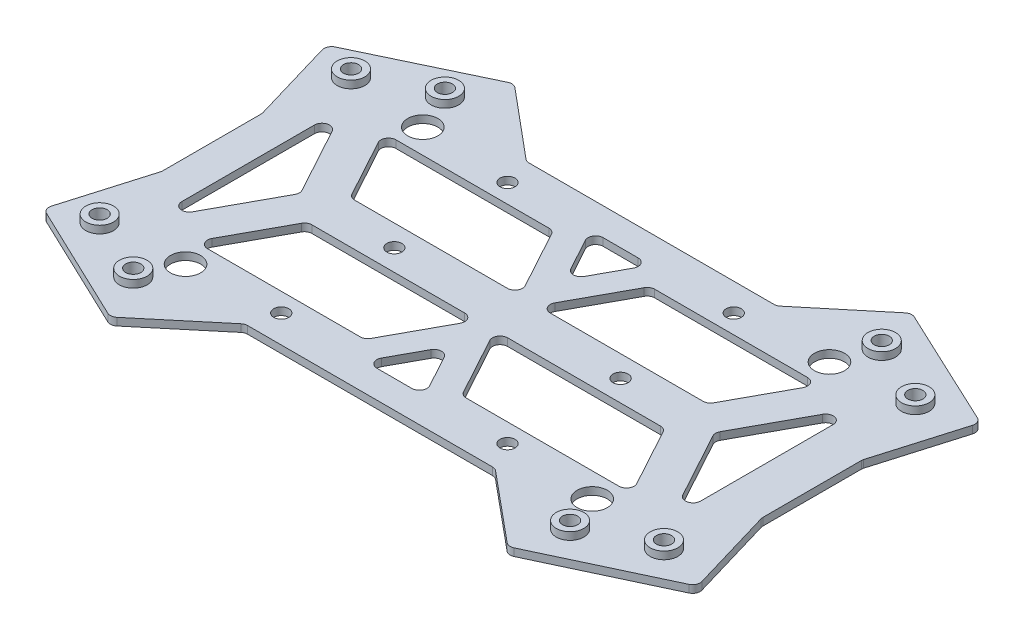
SolidWorks part; units mm, degrees
material "Thornel VCB-20 Carbon Cloth"
ref_plane "Front Plane" through (0, 0, 0) normal (0, 0, 1) x (1, 0, 0)
ref_plane "Top Plane" through (0, 0, 0) normal (0, 1, 0) x (1, 0, 0)
ref_plane "Right Plane" through (0, 0, 0) normal (1, 0, 0) x (0, 0, -1)
sketch "Sketch1" plane through (0, 0, 0) normal (0, 1, 0) x (1, 0, 0)
  line L9 (-39.7187, 39.786) -> (-64.1438, 28.1459) construction
  line L10 (-24.6676, 28.349) -> (-38.1116, 39.583) construction
  line L11 (25.0086, 28) -> (-23.7058, 28) construction
  line L12 (39.5171, 39.5917) -> (25.9666, 28.3457) construction
  line L13 (65.9472, 28.1421) -> (41.1122, 39.7954) construction
  line L14 (-39.7187, 39.786) -> (-64.1438, 28.1459)
  line L22 (-24.6676, 28.349) -> (-38.1116, 39.583)
  line L23 (25.0086, 28) -> (-23.7058, 28)
  line L24 (39.5171, 39.5917) -> (25.9666, 28.3457)
  line L25 (65.9472, 28.1421) -> (41.1122, 39.7954)
  line L26 (-123, 23) -> (-123, -23) construction
  line L27 (100.1, 23) -> (100.1, -23) construction
  line L28 (66.5844, 28) -> (94.45, 28) construction
  line L29 (-64.7892, 28) -> (-118, 28) construction
  line L30 (-123, 23) -> (-123, -23) construction
  line L31 (100.1, 23) -> (100.1, -23) construction
  line L32 (66.5844, 28) -> (94.45, 28) construction
  line L33 (-64.7892, 28) -> (-118, 28) construction
  line L34 (0, 0) -> (0, 28) construction
  line L35 (0, 0) -> (100.1, 0) construction
  line L36 (0, 0) -> (-123, 0) construction
  line L37 (60.6, 0) -> (60.6, 10)
  line L38 (65.9472, 28.1421) -> (60.6, 10)
  line L39 (-58.7938, 0) -> (-58.7938, 10)
  line L40 (-64.1438, 28.1459) -> (-58.7938, 10)
  line L41 (-58.7938, 0) -> (60.6, 0)
  arc A0 (-38.1116, 39.583) -> (-39.7187, 39.786) centre (-39.0734, 38.4319) ccw construction
  arc A1 (-38.1116, 39.583) -> (-39.7187, 39.786) centre (-39.0734, 38.4319) ccw
  circle A14 centre (-43.45, 31) radius 1.5 construction
  circle A15 centre (-56.13, 25) radius 1.5 construction
  arc A16 (-64.7892, 28) -> (-64.1438, 28.1459) centre (-64.7892, 29.5) ccw construction
  arc A29 (-24.6676, 28.349) -> (-23.7058, 28) centre (-23.7058, 29.5) ccw construction
  circle A30 centre (56.13, 25) radius 1.5 construction
  circle A31 centre (43.45, 31) radius 1.5 construction
  arc A32 (25.0086, 28) -> (25.9666, 28.3457) centre (25.0086, 29.5) ccw construction
  arc A33 (41.1122, 39.7954) -> (39.5171, 39.5917) centre (40.475, 38.4375) ccw construction
  arc A34 (65.9472, 28.1421) -> (66.5844, 28) centre (66.5844, 29.5) ccw construction
  circle A35 centre (-43.45, 31) radius 1.5
  circle A36 centre (-56.13, 25) radius 1.5
  arc A37 (-64.7892, 28) -> (-64.1438, 28.1459) centre (-64.7892, 29.5) ccw construction
  arc A39 (-24.6676, 28.349) -> (-23.7058, 28) centre (-23.7058, 29.5) ccw
  circle A40 centre (56.13, 25) radius 1.5
  circle A41 centre (43.45, 31) radius 1.5
  arc A42 (25.0086, 28) -> (25.9666, 28.3457) centre (25.0086, 29.5) ccw
  arc A43 (41.1122, 39.7954) -> (39.5171, 39.5917) centre (40.475, 38.4375) ccw
  arc A44 (65.9472, 28.1421) -> (66.5844, 28) centre (66.5844, 29.5) ccw construction
  dimension "D1" = 10
  dimension "D2" = 39.5
  dimension "D3" = 5.35
  dimension "D4" = 10
extrude "Boss-Extrude1" add sketch "Sketch1" along normal blind 1.5
sketch "Sketch2" plane through (0, 0, 0) normal (0, 1, 0) x (1, 0, 0)
  line L0 (0, 0) -> (0, 50) construction
  line L1 (-6, 22.5) -> (6, 22.5)
  line L2 (6, 22.5) -> (0, 11.5)
  line L3 (0, 11.5) -> (-6, 22.5)
  line L4 (25.0086, 28) -> (-23.7058, 28) construction
  line L5 (25.0086, 28) -> (-23.7058, 28) construction
  line L6 (60.6, 0) -> (60.6, 10) construction
  line L7 (-58.7938, 0) -> (60.6, 0) construction
  line L8 (-58.7938, 10) -> (-58.7938, 0) construction
  line L9 (60.6, 0) -> (60.6, 10) construction
  line L10 (-58.7938, 0) -> (60.6, 0) construction
  line L11 (-58.7938, 10) -> (-58.7938, 0) construction
  line L12 (-58.7938, 4.25) -> (60.6, 4.25) construction
  line L13 (1.7409, 4.25) -> (9.65, 18.75)
  line L14 (9.65, 18.75) -> (43.45, 18.75)
  line L15 (43.45, 18.75) -> (35.5409, 4.25)
  line L16 (35.5409, 4.25) -> (1.7409, 4.25)
  line L17 (-43.45, 18.75) -> (-35.5409, 4.25)
  line L18 (-35.5409, 4.25) -> (-1.7409, 4.25)
  line L19 (-9.65, 18.75) -> (-43.45, 18.75)
  line L20 (-1.7409, 4.25) -> (-9.65, 18.75)
  line L21 (22.5, 22.5) -> (22.5, 0) construction
  line L22 (-22.5, 22.5) -> (-22.5, 0) construction
  line L23 (41.1963, 0) -> (51.6, 19.0734)
  line L24 (51.6, 19.0734) -> (51.6, 0)
  line L25 (51.6, 0) -> (41.1963, 0)
  line L26 (-51.6, 0) -> (-41.1963, 0)
  line L27 (-51.6, 19.0734) -> (-51.6, 0)
  line L28 (-41.1963, 0) -> (-51.6, 19.0734)
  line L29 (21, 0) -> (24, 0)
  line L30 (-24, 0) -> (-21, 0)
  arc A1 (23.6364, 21.5209) -> (21.3636, 23.4791) centre (22.5, 22.5) ccw construction
  circle A6 centre (-40.45, 23.6) radius 1.5 construction
  circle A7 centre (40.45, 23.6) radius 1.5 construction
  circle A8 centre (-40.45, 23.6) radius 1.5 construction
  circle A9 centre (40.45, 23.6) radius 1.5 construction
  circle A10 centre (40.45, 23.6) radius 3
  circle A11 centre (-40.45, 23.6) radius 3
  arc A12 (-24, 0) -> (-21, 0) centre (-22.5, 0) cw
  arc A13 (24, 0) -> (21, 0) centre (22.5, 0) ccw
  circle A14 centre (-22.5, 22.5) radius 1.5
  circle A15 centre (22.5, 22.5) radius 1.5
  point P6 (0, 0)
  point P22 (0, 22.5)
  dimension "D1" = 6
  dimension "D2" = 6
  dimension "D11" = 1.5
  dimension "D12" = 1.5
  dimension "D15" = 3
  dimension "D16" = 3
  dimension "D3" = 50
  dimension "D4" = 11
  dimension "D5" = 5.5
  dimension "D6" = 12
  dimension "D7" = 4.25
  dimension "D8" = 3.75
  dimension "D9" = 3
  dimension "D10" = 5
  dimension "D13" = 7
  dimension "D14" = 9
  dimension "D17" = 22.5
  dimension "D18" = 45
  dimension "D19" = 22.5
extrude "Cut-Extrude3" cut sketch "Sketch2" against normal blind 1.5 and the other way through all
mirror "Mirror1" about plane through (0, 0, 0) normal (0, 0, 1) of bodies 102
fillet "Fillet1" radius 1.5 16 edges at (-35.5409, 0.75, 4.25) (-43.45, 0.75, 18.75) (-9.65, 0.75, 18.75) (-1.7409, 0.75, 4.25) (1.7409, 0.75, 4.25) (9.65, 0.75, 18.75) (43.45, 0.75, 18.75) (35.5409, 0.75, 4.25) (-43.45, 0.75, -18.75) (-35.5409, 0.75, -4.25) (-9.65, 0.75, -18.75) (-1.7409, 0.75, -4.25) (43.45, 0.75, -18.75) (35.5409, 0.75, -4.25) (9.65, 0.75, -18.75) (1.7409, 0.75, -4.25)
fillet "Fillet2" radius 1.5 6 edges at (-51.6, 0.75, -19.0734) (-51.6, 0.75, 19.0734) (-41.1963, 0.75, 0) (41.1963, 0.75, 0) (51.6, 0.75, 19.0734) (51.6, 0.75, -19.0734)
fillet "Fillet3" radius 1.5 6 edges at (-6, 0.75, 22.5) (0, 0.75, 11.5) (6, 0.75, 22.5) (0, 0.75, -11.5) (6, 0.75, -22.5) (-6, 0.75, -22.5)
fillet "Fillet4" radius 1.5 8 edges at (-58.7938, 0.75, -10) (-64.1438, 0.75, -28.1459) (-64.1438, 0.75, 28.1459) (-58.7938, 0.75, 10) (65.9472, 0.75, 28.1421) (60.6, 0.75, 10) (60.6, 0.75, -10) (65.9472, 0.75, -28.1421)
sketch "Sketch3" plane through (0, 1.5, 0) normal (0, 1, 0) x (1, 0, 0)
  circle A0 centre (-43.45, 31) radius 1.5 construction
  circle A1 centre (-56.13, 25) radius 1.5 construction
  circle A2 centre (56.13, 25) radius 1.5 construction
  circle A3 centre (43.45, 31) radius 1.5 construction
  circle A4 centre (-43.45, 31) radius 1.5
  circle A5 centre (-56.13, 25) radius 1.5
  circle A6 centre (56.13, 25) radius 1.5
  circle A7 centre (43.45, 31) radius 1.5
  circle A8 centre (-56.13, 25) radius 2.75
  circle A9 centre (-43.45, 31) radius 2.75
  circle A10 centre (43.45, 31) radius 2.75
  circle A11 centre (56.13, 25) radius 2.75
  dimension "D1" = 5.5
extrude "Boss-Extrude2" add sketch "Sketch3" along normal blind 1.5
mirror "Mirror2" about plane through (0, 0, 0) normal (0, 0, 1) of "Boss-Extrude2"
